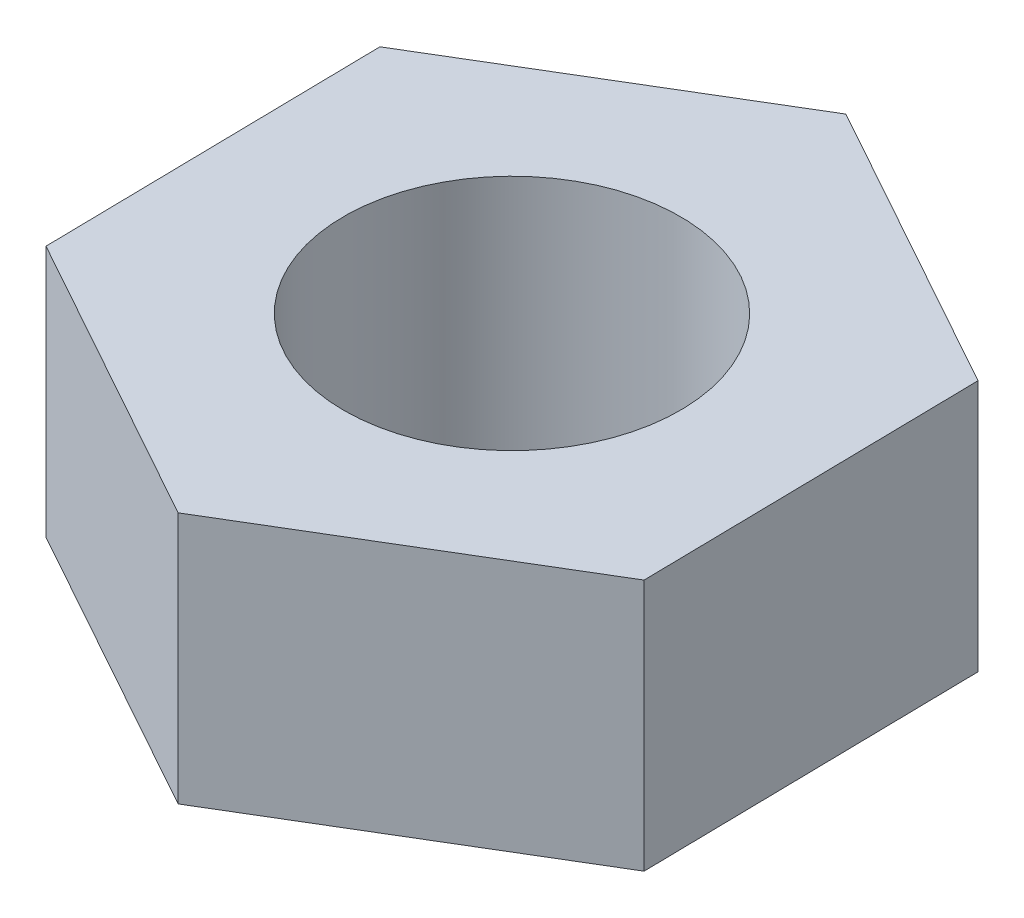
SolidWorks part; units mm, degrees
ref_plane "Front" through (0, 0, 0) normal (0, 0, 1) x (1, 0, 0)
ref_plane "Top" through (0, 0, 0) normal (0, 1, 0) x (1, 0, 0)
ref_plane "Right" through (0, 0, 0) normal (1, 0, 0) x (0, 0, -1)
sketch "Sketch1" plane through (0, 0, 0) normal (0, 1, 0) x (1, 0, 0)
  line L1 (3.4655, 2.0793) -> (-0.068, 4.0409)
  line L2 (-0.068, 4.0409) -> (-3.5335, 1.9616)
  line L3 (-3.5335, 1.9616) -> (-3.4655, -2.0793)
  line L4 (-3.4655, -2.0793) -> (0.068, -4.0409)
  line L5 (0.068, -4.0409) -> (3.5335, -1.9616)
  line L6 (3.5335, -1.9616) -> (3.4655, 2.0793)
  circle A0 centre (0, 0) radius 3.5 construction
  circle A1 centre (0, 0) radius 2
  dimension "D2" = 4
  dimension "D1" = 7
extrude "Boss-Extrude1" add sketch "Sketch1" along normal blind 3
